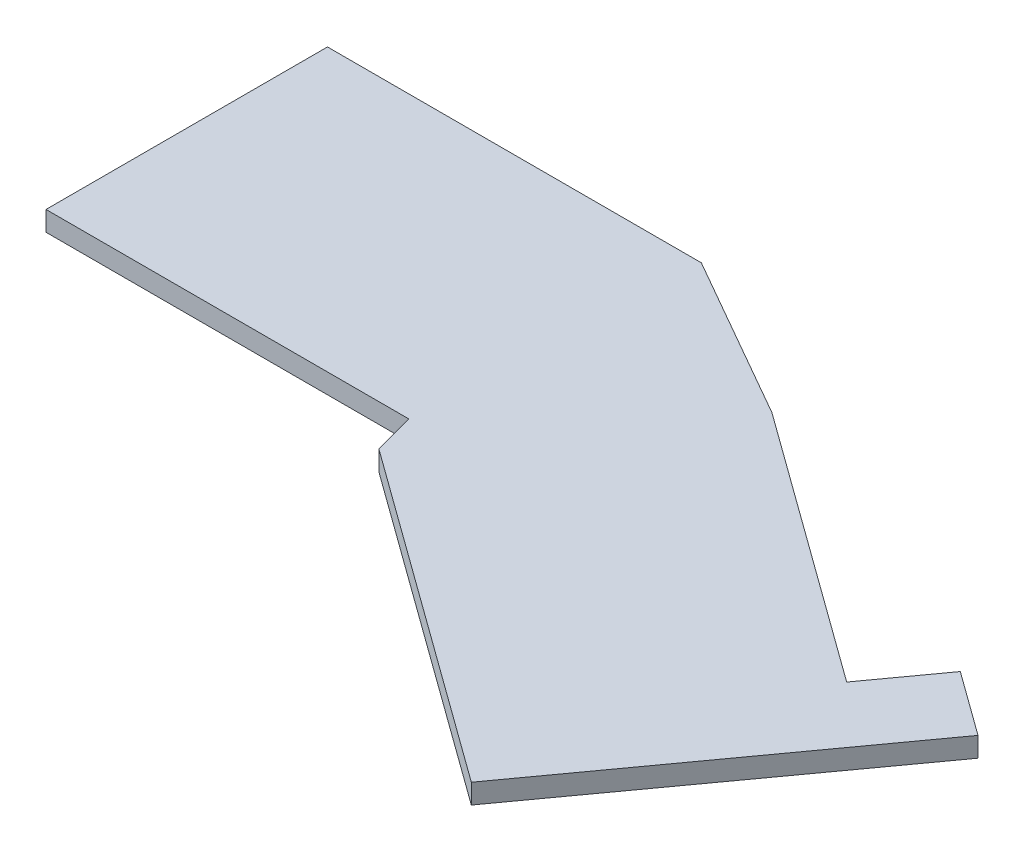
SolidWorks part; units mm, degrees
ref_plane "前视基准面" through (0, 0, 0) normal (0, 0, 1) x (1, 0, 0)
ref_plane "上视基准面" through (0, 0, 0) normal (0, 1, 0) x (1, 0, 0)
ref_plane "右视基准面" through (0, 0, 0) normal (1, 0, 0) x (0, 0, -1)
sketch "草图1" plane through (0, 0, 0) normal (0, 1, 0) x (1, 0, 0)
  line L10 (0, 30.75) -> (0, -30.75)
  line L11 (0, -30.75) -> (82.2087, -30.75)
  line L12 (82.2087, -30.75) -> (84.8423, -40.5614)
  line L13 (84.8423, -40.5614) -> (159.6143, -94.6873)
  line L14 (159.6143, -94.6873) -> (206.5241, -29.884)
  line L15 (206.5241, -29.884) -> (193.9685, -20.7952)
  line L16 (193.9685, -20.7952) -> (183.1206, -35.781)
  line L17 (183.1206, -35.781) -> (120.599, 9.4771)
  line L18 (120.599, 9.4771) -> (83.4177, 30.75)
  line L19 (83.4177, 30.75) -> (0, 30.75)
  line L20 (-1.25, 32) -> (-1.25, -32)
  line L21 (-1.25, -32) -> (81.25, -32)
  line L22 (81.25, -32) -> (83.75, -41.3138)
  line L23 (83.75, -41.3138) -> (159.8939, -96.4328)
  line L24 (159.8939, -96.4328) -> (208.2696, -29.6044)
  line L25 (208.2696, -29.6044) -> (193.6889, -19.0497)
  line L26 (193.6889, -19.0497) -> (182.841, -34.0355)
  line L27 (182.841, -34.0355) -> (121.2778, 10.5288)
  line L28 (121.2778, 10.5288) -> (83.75, 32)
  line L29 (83.75, 32) -> (-1.25, 32)
  dimension "D1" = 1.25
extrude "凸台-拉伸1" add sketch "草图1" against normal blind 2
sketch "草图2" plane through (0, 0, 0) normal (0, 1, 0) x (1, 0, 0)
  line L10 (-1.25, 32) -> (-1.25, -32)
  line L11 (-1.25, -32) -> (81.25, -32)
  line L12 (81.25, -32) -> (83.75, -41.3138)
  line L13 (83.75, -41.3138) -> (159.8939, -96.4328)
  line L14 (159.8939, -96.4328) -> (208.2696, -29.6044)
  line L15 (208.2696, -29.6044) -> (193.6889, -19.0497)
  line L16 (193.6889, -19.0497) -> (182.841, -34.0355)
  line L17 (182.841, -34.0355) -> (121.2778, 10.5288)
  line L18 (121.2778, 10.5288) -> (83.75, 32)
  line L19 (83.75, 32) -> (-1.25, 32)
extrude "凸台-拉伸2" add sketch "草图2" along normal blind 2.5
